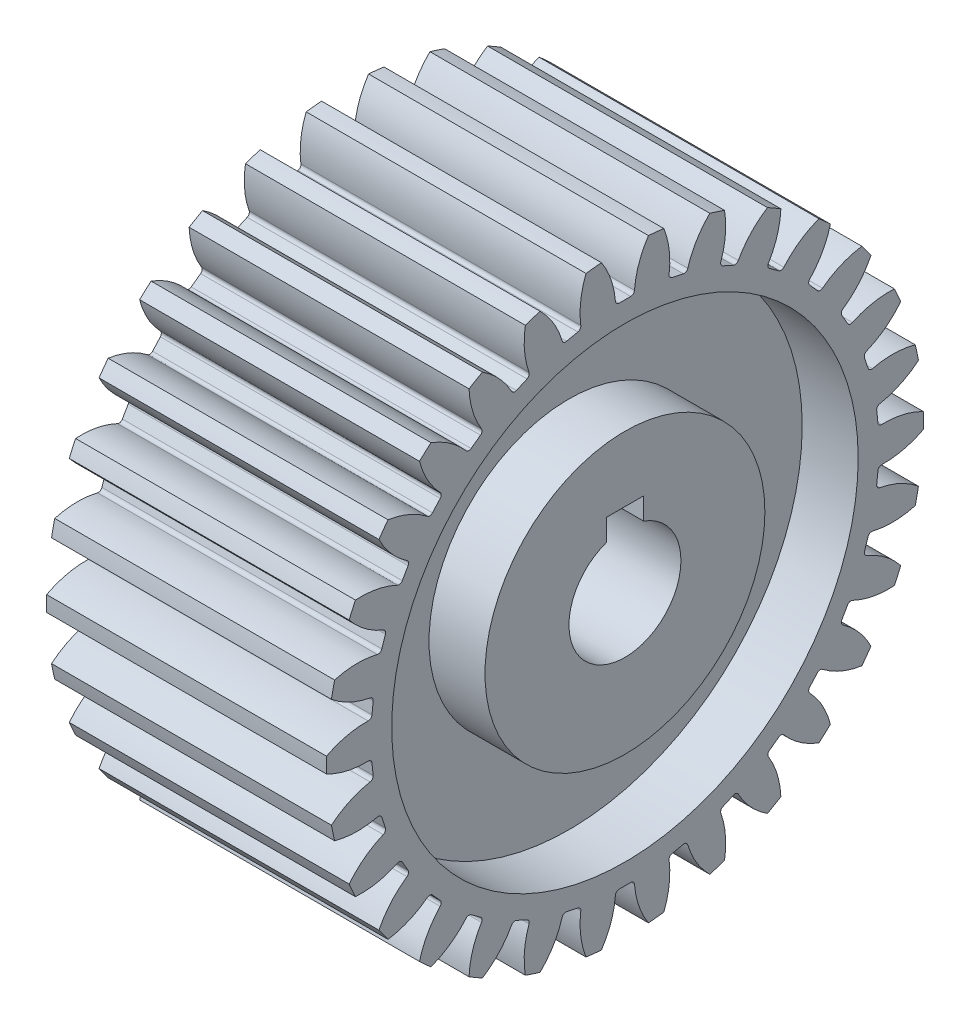
SolidWorks part; units mm, degrees
ref_plane "Front Plane" through (0, 0, 0) normal (0, 0, 1) x (1, 0, 0)
ref_plane "Top Plane" through (0, 0, 0) normal (0, 1, 0) x (1, 0, 0)
ref_plane "Right Plane" through (0, 0, 0) normal (1, 0, 0) x (0, 0, -1)
sketch "Sketch1" plane through (0, 0, 0) normal (1, 0, 0) x (0, 0, -1)
  circle A0 centre (0, 0) radius 16
  dimension "D1" = 32
extrude "circular - extrude" add sketch "Sketch1" along normal mid plane 15
sketch "Sketch3" plane through (7.5, 0, 0) normal (1, 0, 0) x (0, 0, -1)
  line L2 (-1, 2.8284) -> (-1, 4)
  line L3 (-1, 4) -> (1, 4)
  line L4 (1, 2.8284) -> (1, 4)
  arc A0 (-1, 2.8284) -> (1, 2.8284) centre (0, 0) ccw
  point P1 (0, 4)
  point P3 (0, 3)
  dimension "D1" = 6
  dimension "D2" = 2
  dimension "D3" = 1
  dimension "D4" = 1
extrude "Cut- circular + top rectangle" cut sketch "Sketch3" against normal through all
sketch "Sketch4" plane through (7.5, 0, 0) normal (1, 0, 0) x (0, 0, -1)
  circle A0 centre (0, 0) radius 7.5
  circle A1 centre (0, 0) radius 12.5
  dimension "D1" = 25
  dimension "D2" = 15
extrude "extrude cut ( rad: 25 -15)" cut sketch "Sketch4" against normal blind 3
mirror "mirror - extrude cut" about plane through (0, 0, 0) normal (1, 0, 0) of "extrude cut ( rad: 25 -15)"
sketch "Sketch5" plane through (7.5, 0, 0) normal (1, 0, 0) x (0, 0, -1)
  line L0 (0, 0) -> (0, 16) construction
  line L1 (0, 16) -> (0, 18.1227) construction
  line L2 (-0.3114, 13.6) -> (0.3114, 13.6)
  line L3 (0.5, 13.6) -> (0.5, 12.49)
  circle A0 centre (0, 0) radius 16 construction
  circle A1 centre (0, 0) radius 12.5 construction
  arc A2 (0.5108, 13.7843) -> (2.08, 16.88) centre (5.0567, 13.4256) cw
  arc A3 (-0.5108, 13.7843) -> (-2.08, 16.88) centre (-5.0567, 13.4256) ccw
  arc A4 (-2.08, 16.88) -> (2.08, 16.88) centre (0, 10.8511) cw
  arc A5 (-0.5108, 13.7843) -> (-0.3114, 13.6) centre (-0.3114, 13.8) ccw
  arc A6 (0.5108, 13.7843) -> (0.3114, 13.6) centre (0.3114, 13.8) cw
  point P14 (0.9894, 15.4873)
  point P16 (0, 13.6)
  point P21 (-0.5, 13.6)
  circle M5 centre (0, 0) radius 16
  dimension "D3" = 1.58
  dimension "D6" = 0.2
  dimension "D7" = 6.3777
  dimension "D1" = 0.5
  dimension "D2" = 13.6
  dimension "D4" = 3.28
  dimension "D5" = 4.56
extrude "Cut - tooth" cut sketch "Sketch5" against normal through all contours A6 A2 A3 A5 L2 M5
pattern_circular "30 nos" count 30 over 360 about axis through (0, 0, 0) along (1, 0, 0) of "Cut - tooth"
